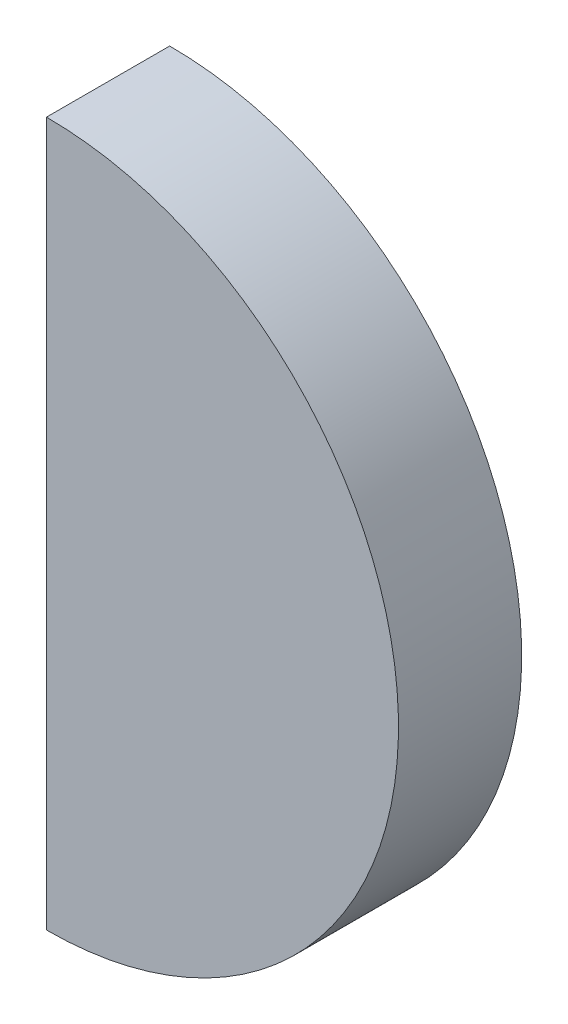
SolidWorks part; units mm, degrees
ref_plane "Plan de face" through (0, 0, 0) normal (0, 0, 1) x (1, 0, 0)
ref_plane "Plan de dessus" through (0, 0, 0) normal (0, 1, 0) x (1, 0, 0)
ref_plane "Plan de droite" through (0, 0, 0) normal (1, 0, 0) x (0, 0, -1)
sketch "Esquisse1" plane through (0, 0, 0) normal (0, 0, 1) x (1, 0, 0)
  line L0 (0, 200) -> (0, -200)
  circle A0 centre (0, 0) radius 200
  dimension "D1" = 400
extrude "Boss.-Extru.1" add sketch "Esquisse1" along normal blind 70 contours L0 A0
